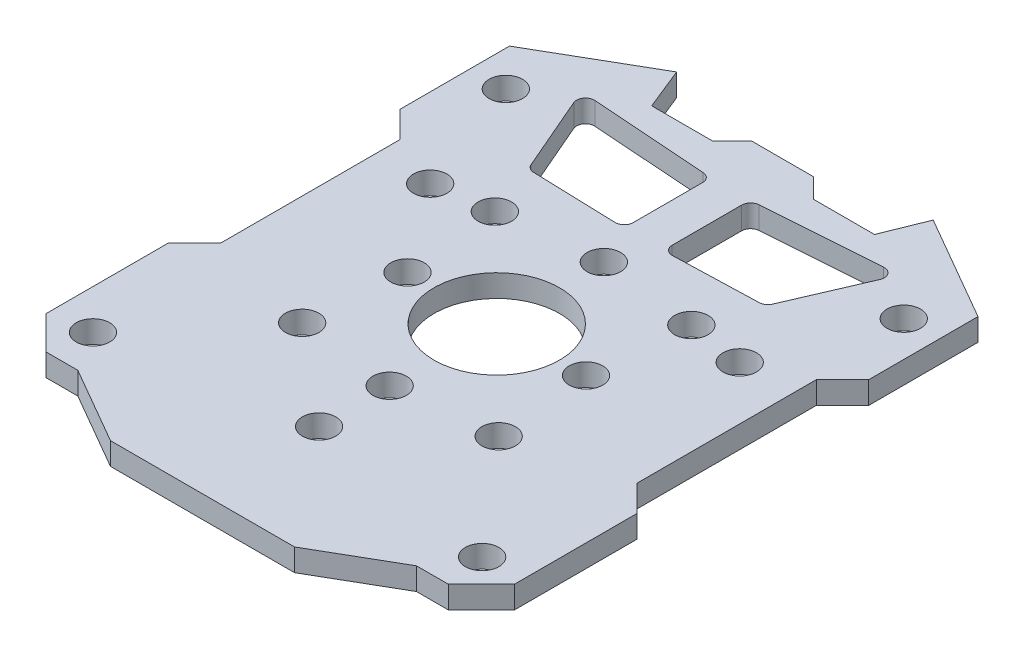
SolidWorks part; units mm, degrees
ref_plane "Front Plane" through (0, 0, 0) normal (0, 0, 1) x (1, 0, 0)
ref_plane "Top Plane" through (0, 0, 0) normal (0, 1, 0) x (1, 0, 0)
ref_plane "Right Plane" through (0, 0, 0) normal (1, 0, 0) x (0, 0, -1)
sketch "Sketch1" plane through (0, 0, 0) normal (0, 1, 0) x (1, 0, 0)
  line L0 (0, 0) -> (0, 52) construction
  line L1 (2.75, 52) -> (-2.75, 52)
  line L2 (-2.75, 52) -> (-4.5, 50.25)
  line L3 (-4.5, 50.25) -> (-9.9849, 50.25)
  line L4 (-9.9849, 50.25) -> (-11.5, 54)
  line L5 (-11.5, 54) -> (-21, 48.5152)
  line L6 (-21, 48.5152) -> (-21, 38.7198)
  line L7 (-21, 38.7198) -> (-18.65, 36.3698)
  line L8 (-18.65, 36.3698) -> (-18.65, 20.3198)
  line L9 (-18.65, 20.3198) -> (-21, 17.9698)
  line L10 (-21, 17.9698) -> (-21, 6.9698)
  line L11 (-21, 6.9698) -> (-18.0302, 4)
  line L12 (-18.0302, 4) -> (-15.1782, 4)
  line L13 (-15.1782, 4) -> (-8.25, 0)
  line L14 (-8.25, 0) -> (8.25, 0)
  line L15 (15.1782, 4) -> (8.25, 0)
  line L16 (18.0302, 4) -> (15.1782, 4)
  line L17 (21, 6.9698) -> (18.0302, 4)
  line L18 (21, 17.9698) -> (21, 6.9698)
  line L19 (18.65, 20.3198) -> (21, 17.9698)
  line L20 (18.65, 36.3698) -> (18.65, 20.3198)
  line L21 (21, 38.7198) -> (18.65, 36.3698)
  line L22 (21, 48.5152) -> (21, 38.7198)
  line L23 (11.5, 54) -> (21, 48.5152)
  line L24 (9.9849, 50.25) -> (11.5, 54)
  line L25 (4.5, 50.25) -> (9.9849, 50.25)
  line L26 (2.75, 52) -> (4.5, 50.25)
  line L27 (-18.0302, 4) -> (-25.0644, 4) construction
  line L28 (-18.65, 20.3198) -> (-34.6393, 20.3198) construction
  line L29 (-2.75, 52) -> (-4.9751, 52) construction
  line L30 (-11.5, 54) -> (-20.2691, 54) construction
  line L31 (-8.25, 0) -> (-15.4287, 0) construction
  dimension "D4" = 5.5
  dimension "D1" = 45
  dimension "D2" = 45
  dimension "D3" = 42
  dimension "D5" = 16.5
  dimension "D6" = 4.2
  dimension "D7" = 54
  dimension "D8" = 45
  dimension "D9" = 23
  dimension "D10" = 1.75
  dimension "D11" = 52
  dimension "D12" = 30
  dimension "D13" = 20.75
  dimension "D14" = 11
  dimension "D15" = 4
  dimension "D16" = 37.3
  dimension "D17" = 82
  dimension "D18" = 30
extrude "Boss-Extrude1" add sketch "Sketch1" along normal blind 2
sketch "Sketch2" plane through (0, 2, 0) normal (0, 1, 0) x (1, 0, 0)
  line L0 (0, 0) -> (0, 52) construction
  line L1 (2.75, 52) -> (-2.75, 52) construction
  line L2 (0, 26.375) -> (-8, 26.375) construction
  line L3 (0, 16.775) -> (-8.8074, 17.7389) construction
  line L4 (-8.8074, 17.7389) -> (0, 26.375) construction
  line L5 (-8.8074, 17.7389) -> (-17.4424, 7.6233) construction
  line L6 (-17.4424, 7.6233) -> (0, 10.45) construction
  line L7 (0, 35.975) -> (-8.8074, 35.0111) construction
  line L8 (-8.8074, 35.0111) -> (0, 26.375) construction
  line L9 (-8.8074, 35.0111) -> (-13.8751, 34.2811) construction
  line L10 (-8, 26.375) -> (-13.8751, 34.2811) construction
  line L11 (-17.8357, 45.0243) -> (-13.8751, 34.2811) construction
  line L12 (-17.8357, 45.0243) -> (0, 35.975) construction
  line L13 (0, 34.475) -> (0, 18.275) construction
  circle A0 centre (-17.8357, 45.0243) radius 1.5
  circle A1 centre (-17.4424, 7.6233) radius 1.5
  circle A2 centre (0, 10.45) radius 1.5
  circle A3 centre (0, 16.775) radius 1.5
  circle A4 centre (0, 26.375) radius 5.625
  circle A5 centre (-8.8074, 17.7389) radius 1.5
  circle A6 centre (-8, 26.375) radius 1.5
  circle A7 centre (-13.8751, 34.2811) radius 1.5
  circle A8 centre (-8.8074, 35.0111) radius 1.5
  circle A9 centre (0, 35.975) radius 1.5
  point P26 (-6.5, 26.375)
  point P27 (0, 32)
  point P28 (0, 32)
  point P30 (0, 0)
  point P31 (0, 20.75)
  point P32 (-7.3163, 17.5757)
  point P33 (0, 11.95)
  point P34 (-1.4911, 16.9382)
  point P35 (-7.7364, 18.7891)
  point P36 (-4.0163, 22.4368)
  point P37 (-9.7813, 16.5981)
  point P38 (-16.4686, 8.7641)
  point P39 (-15.9618, 7.8632)
  point P40 (-1.4807, 10.21)
  point P41 (-12.3904, 34.4949)
  point P42 (-10.2921, 34.7972)
  point P43 (-12.9804, 33.0771)
  point P44 (-8.8947, 27.579)
  point P45 (-17.3168, 43.6169)
  point P46 (-14.3939, 35.6885)
  point P47 (-16.498, 44.3456)
  point P48 (-1.3377, 36.6537)
  point P49 (0, 0)
  dimension "D1" = 3
  dimension "D2" = 11.25
  dimension "D3" = 6.5
  dimension "D4" = 20
  dimension "D5" = 16.2
  dimension "D7" = 8.8
  dimension "D8" = 5.86
  dimension "D9" = 5.21
  dimension "D10" = 10.3
  dimension "D11" = 14.67
  dimension "D12" = 2.12
  dimension "D13" = 6.85
  dimension "D14" = 8.45
  dimension "D15" = 17
extrude "Cut-Extrude1" cut sketch "Sketch2" against normal up to surface (2 mm away) up to face at (0, 0, -29.4896)
mirror "Mirror1" about plane through (0, 0, 0) normal (1, 0, 0) of "Cut-Extrude1"
sketch "Sketch3" plane through (0, 2, 0) normal (0, 1, 0) x (1, 0, 0)
  line L0 (-2.4931, 47.3776) -> (-12.9374, 48.1218)
  line L1 (-13.7288, 47.007) -> (-10.8263, 40.2778)
  line L2 (-10.117, 39.795) -> (-2.5753, 39.5565)
  line L3 (0, 39.475) -> (0, 47.2) construction
  line L4 (10.117, 39.795) -> (2.5753, 39.5565)
  line L5 (13.7288, 47.007) -> (10.8263, 40.2778)
  line L6 (2.4931, 47.3776) -> (12.9374, 48.1218)
  line L7 (2.75, 52) -> (-2.75, 52) construction
  line L8 (-1.75, 46.5797) -> (-1.75, 40.3561)
  line L9 (1.75, 46.5797) -> (1.75, 40.3561)
  line L10 (-1.75, 39.5304) -> (0, 39.475) construction
  line L11 (0, 39.475) -> (1.75, 39.5304) construction
  line L12 (1.75, 47.3247) -> (0, 47.2) construction
  line L13 (0, 47.2) -> (-1.75, 47.3247) construction
  arc A0 (13.7288, 47.007) -> (12.9374, 48.1218) centre (12.9942, 47.3238) ccw
  arc A1 (10.117, 39.795) -> (10.8263, 40.2778) centre (10.0917, 40.5946) ccw
  arc A2 (-10.8263, 40.2778) -> (-10.117, 39.795) centre (-10.0917, 40.5946) ccw
  arc A3 (-12.9374, 48.1218) -> (-13.7288, 47.007) centre (-12.9942, 47.3238) ccw
  circle A4 centre (0, 35.975) radius 1.5 construction
  circle A5 centre (-8.8074, 35.0111) radius 1.5 construction
  circle A6 centre (-17.8357, 45.0243) radius 1.5 construction
  arc A7 (1.75, 40.3561) -> (2.5753, 39.5565) centre (2.55, 40.3561) ccw
  arc A8 (-1.75, 40.3561) -> (-2.5753, 39.5565) centre (-2.55, 40.3561) cw
  arc A9 (1.75, 46.5797) -> (2.4931, 47.3776) centre (2.55, 46.5797) cw
  arc A10 (-1.75, 46.5797) -> (-2.4931, 47.3776) centre (-2.55, 46.5797) ccw
  point P13 (14.25, 48.2153)
  point P16 (10.625, 39.8111)
  point P19 (-10.625, 39.8111)
  point P22 (-14.25, 48.2153)
  dimension "D1" = 0.8
  dimension "D9" = 0.8
  dimension "D2" = 3.5
  dimension "D3" = 4.8
  dimension "D4" = 28.5
  dimension "D5" = 21.25
  dimension "D6" = 4.8
  dimension "D7" = 4.8
  dimension "D8" = 3.5
extrude "Cut-Extrude2" cut sketch "Sketch3" against normal up to surface (2 mm away) up to face at (17.8357, 0, -43.5243)
